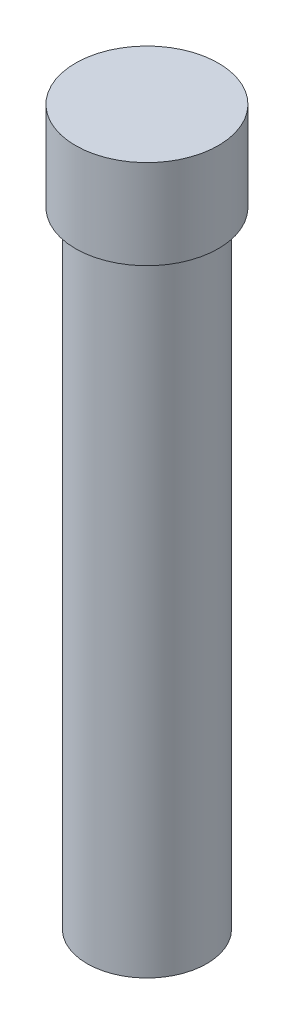
SolidWorks part; units mm, degrees
ref_plane "前视基准面" through (0, 0, 0) normal (0, 0, 1) x (1, 0, 0)
ref_plane "上视基准面" through (0, 0, 0) normal (0, 1, 0) x (1, 0, 0)
ref_plane "右视基准面" through (0, 0, 0) normal (1, 0, 0) x (0, 0, -1)
other "Configuration Table"
sketch "草图1" plane through (0, 0, 0) normal (0, 1, 0) x (1, 0, 0)
  circle A0 centre (0, 0) radius 3.35
  dimension "D1" = 6.7
extrude "凸台-拉伸1" add sketch "草图1" along normal blind 35 contours A0
sketch "草图2" plane through (0, 35, 0) normal (0, 1, 0) x (1, 0, 0)
  circle A0 centre (0, 0) radius 4
  dimension "D1" = 8
extrude "凸台-拉伸2" add sketch "草图2" along normal blind 5
